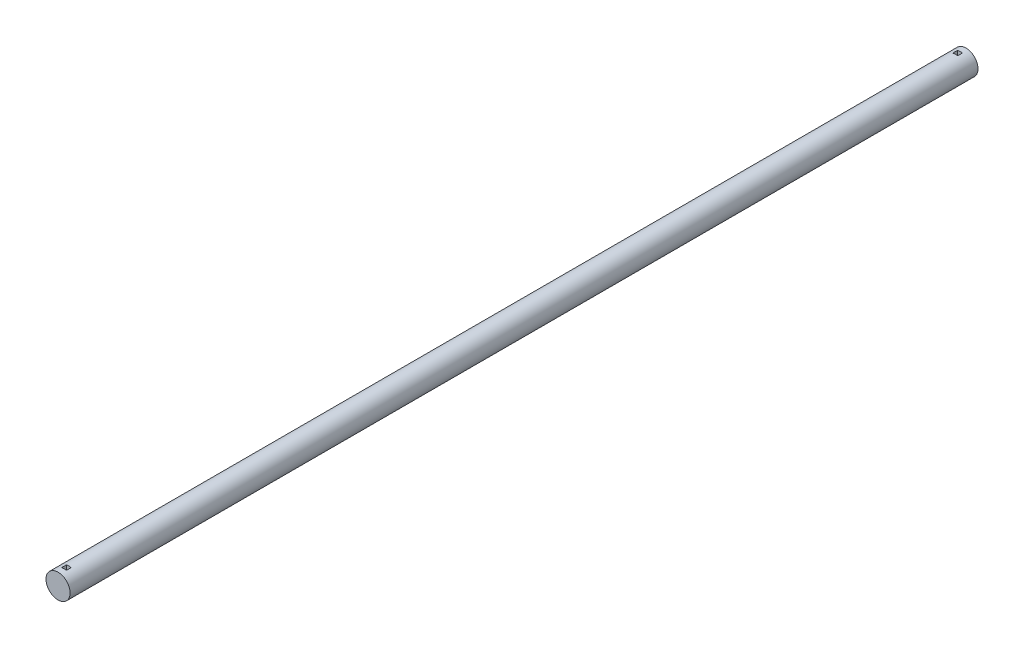
SolidWorks part; units mm, degrees
material "Oak"
ref_plane "Front" through (0, 0, 0) normal (0, 0, 1) x (1, 0, 0)
ref_plane "Top" through (0, 0, 0) normal (0, 1, 0) x (1, 0, 0)
ref_plane "Right" through (0, 0, 0) normal (1, 0, 0) x (0, 0, -1)
sketch "Sketch1" plane through (0, 0, 0) normal (0, 0, 1) x (1, 0, 0)
  line L0 (0, 0) -> (-50.5, 0) construction
  circle A0 centre (0, 0) radius 50.5
  dimension "D1" = 101
extrude "Boss-Extrude1" add sketch "Sketch1" along normal blind 3800
sketch "Sketch2" plane through (0, 0, 0) normal (0, 1, 0) x (1, 0, 0)
  line L0 (50.5, 0) -> (-50.5, 0) construction
  line L1 (-10, -25) -> (10, -25)
  line L2 (-10, -25) -> (-10, -45)
  line L3 (-10, -45) -> (10, -45)
  line L4 (10, -25) -> (10, -45)
  line L5 (0, 0) -> (0, -26.0194) construction
  line L6 (0, 0) -> (-50.5, 0) construction
  dimension "D1" = 25
  dimension "D2" = 20
  dimension "D3" = 20
extrude "Cut-Extrude1" cut sketch "Sketch2" against normal through all both and the other way through all
ref_plane "Plane1" through (0, 0, 1900) normal (0, 0, -1) x (-1, 0, 0)
mirror "Mirror1" about plane through (0, 0, 1900) normal (0, 0, -1) of "Cut-Extrude1"
